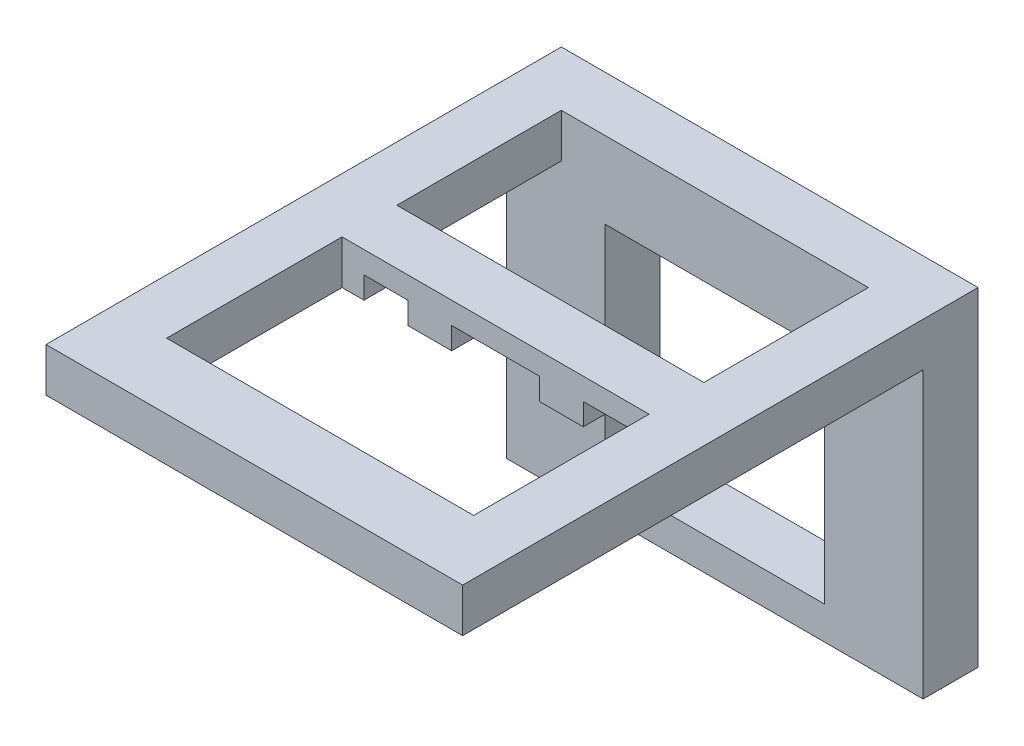
SolidWorks part; units mm, degrees
ref_plane "前视基准面" through (0, 0, 0) normal (0, 0, 1) x (1, 0, 0)
ref_plane "上视基准面" through (0, 0, 0) normal (0, 1, 0) x (1, 0, 0)
ref_plane "右视基准面" through (0, 0, 0) normal (1, 0, 0) x (0, 0, -1)
other "Configuration Table"
sketch "草图3" plane through (0, 0, 0) normal (0, 0, 1) x (1, 0, 0)
  line L0 (5, -2.3971) -> (5, 9.1029)
  line L2 (-5, 7.6029) -> (5, 7.6029)
  line L11 (-5, -2.3971) -> (-5, 9.1029)
  line L12 (5, -2.3971) -> (-5, -2.3971)
  line L17 (9.5, 9.1029) -> (-9.5, 9.1029)
  line L18 (9.5, 9.1029) -> (9.5, -3.8971)
  line L19 (9.5, -3.8971) -> (-9.5, -3.8971)
  line L20 (-9.5, 9.1029) -> (-9.5, -3.8971)
  arc A2 (2.9155, -2.1471) -> (-2.9155, -2.1471) centre (0, 1.6029) ccw construction
  dimension "D2" = 1.5
  dimension "D3" = 19
  dimension "D4" = 9.5
  dimension "D5" = 7.5
  dimension "D1" = 11.5
  dimension "D6" = 10
  dimension "D8" = 1.5
  dimension "D7" = 5
extrude "凸台-拉伸1" add sketch "草图3" along normal blind 2.5
sketch "草图4" plane through (0, 9.1029, 0) normal (0, 1, 0) x (1, 0, 0)
  line L1 (9.5, 0) -> (-9.5, 0)
  line L2 (9.5, 0) -> (9.5, -23.5)
  line L3 (9.5, -23.5) -> (-9.5, -23.5)
  line L4 (-9.5, 0) -> (-9.5, -23.5)
  line L6 (7, -2.5) -> (7, -10)
  line L7 (7, -10) -> (-7, -10)
  line L8 (-7, -2.5) -> (-7, -10)
  line L9 (9.5, -2.5) -> (-9.5, -2.5)
  line L10 (7, -20.5) -> (-7, -20.5)
  line L11 (7, -12.5) -> (-7, -12.5)
  line L12 (7, -12.5) -> (7, -20.5)
  line L13 (-7, -12.5) -> (-7, -20.5)
  line L14 (0, 0) -> (0, -23.5) construction
  point P18 (0, -10)
  point P26 (0, -20.5)
  line M15 (9.5, 0) -> (-9.5, 0)
  line M16 (-9.5, 0) -> (-9.5, -2.5)
  line M17 (-9.5, -2.5) -> (9.5, -2.5)
  line M18 (9.5, -2.5) -> (9.5, 0)
  dimension "D1" = 21
  dimension "D2" = 2.5
  dimension "D3" = 7.5
  dimension "D4" = 2.5
  dimension "D5" = 3
extrude "凸台-拉伸2" add sketch "草图4" along normal blind 2 contours L14 L9 M15 M17 M18 | L14 L1 M16 M17 | L14 L7 L8 L4 L3 L10 L13 L11 M17 | L7 L14 L11 L12 L10 L3 L2 L6 M17
sketch "草图6" plane through (0, 0, 2.5) normal (0, 0, 1) x (1, 0, 0)
  line L1 (-6, 10.1029) -> (-4, 10.1029)
  line L2 (-6, 10.1029) -> (-6, 9.1029)
  line L3 (-6, 9.1029) -> (-4, 9.1029)
  line L4 (-4, 10.1029) -> (-4, 9.1029)
  line L5 (4, 10.1029) -> (6, 10.1029)
  line L6 (4, 10.1029) -> (4, 9.1029)
  line L7 (4, 9.1029) -> (6, 9.1029)
  line L8 (6, 10.1029) -> (6, 9.1029)
  line L9 (9.5, 9.1029) -> (-9.5, 9.1029) construction
  line L10 (-2, 10.1029) -> (2, 10.1029)
  line L11 (-2, 10.1029) -> (-2, 9.1029)
  line L12 (-2, 9.1029) -> (2, 9.1029)
  line L13 (2, 10.1029) -> (2, 9.1029)
  line L16 (0, 11.1029) -> (0, 9.1029) construction
  line L17 (9.5, 11.1029) -> (-9.5, 11.1029) construction
  dimension "D1" = 1
  dimension "D2" = 4
  dimension "D3" = 2
  dimension "D4" = 2
extrude "切除-拉伸1" cut sketch "草图6" along normal up to next
